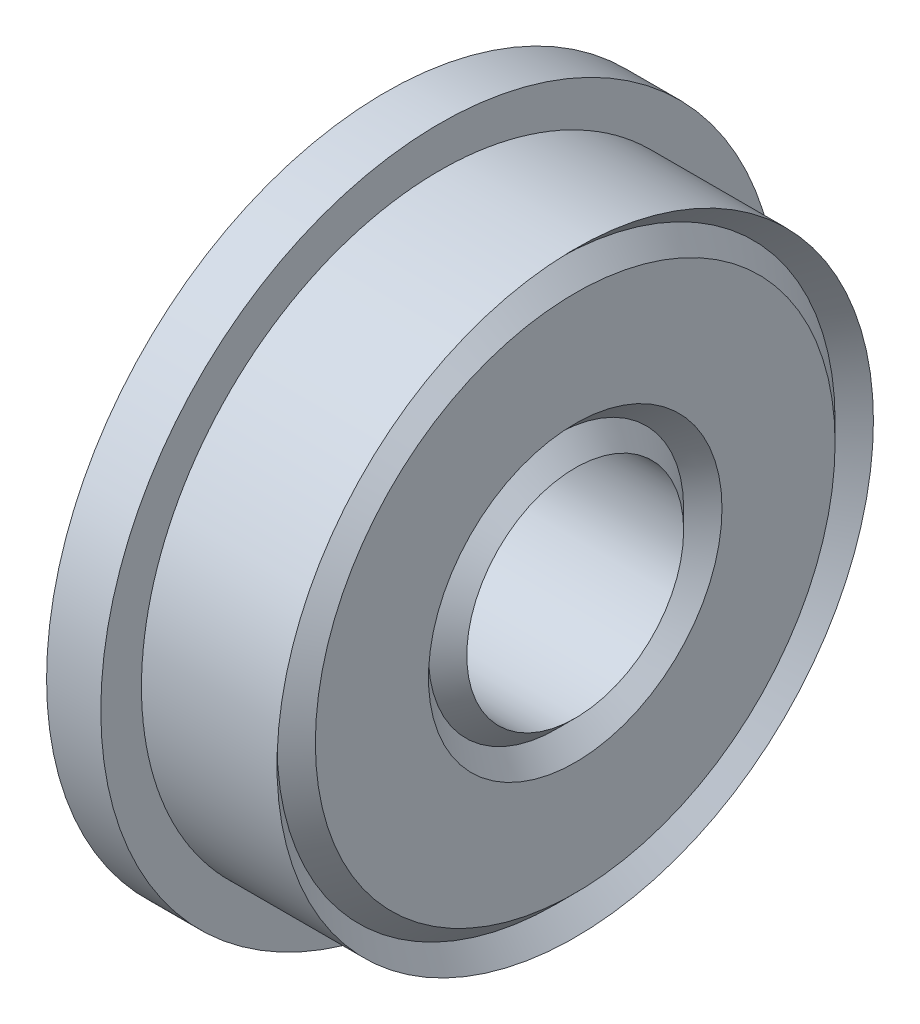
SolidWorks part; units mm, degrees
ref_plane "前视基准面" through (0, 0, 0) normal (0, 0, 1) x (1, 0, 0)
ref_plane "上视基准面" through (0, 0, 0) normal (0, 1, 0) x (1, 0, 0)
ref_plane "右视基准面" through (0, 0, 0) normal (1, 0, 0) x (0, 0, -1)
sketch "草图1" plane through (0, 0, 0) normal (0, 1, 0) x (1, 0, 0)
  line L0 (-7, -4) -> (0, -4)
  line L1 (0, 0) -> (-7, 0)
  line L2 (0, 0) -> (0, -11)
  line L3 (0, -11) -> (-7, -11)
  line L4 (-7, 0) -> (-7, -11)
  line L5 (-7, -11) -> (-6.2929, -10.2929)
  line L6 (-6.2929, -10.2929) -> (-7, -9.5858)
  line L7 (-7, -9.5858) -> (-7, -5.4142)
  line L8 (-7, -5.4142) -> (-6.2929, -4.7071)
  line L9 (-6.2929, -4.7071) -> (-7, -4)
  line L10 (0, -11) -> (-0.7071, -10.2929)
  line L11 (-0.7071, -10.2929) -> (0, -9.5858)
  line L12 (0, -5.4142) -> (-0.7071, -4.7071)
  line L13 (-0.7071, -4.7071) -> (0, -4)
  dimension "D1" = 7
  dimension "D2" = 11
  dimension "D3" = 4
  dimension "D4" = 1
  dimension "D5" = 90
  dimension "D6" = 1
revolve "旋转1" add sketch "草图1" angle 360 about L1
sketch "草图2" plane through (-7, 0, 0) normal (-1, 0, 0) x (0, 0, 1)
  circle A0 centre (0, 0) radius 12.5
  circle A1 centre (0, 0) radius 11
  dimension "D2" = 25
extrude "凸台-拉伸1" add sketch "草图2" against normal blind 2 separate body
